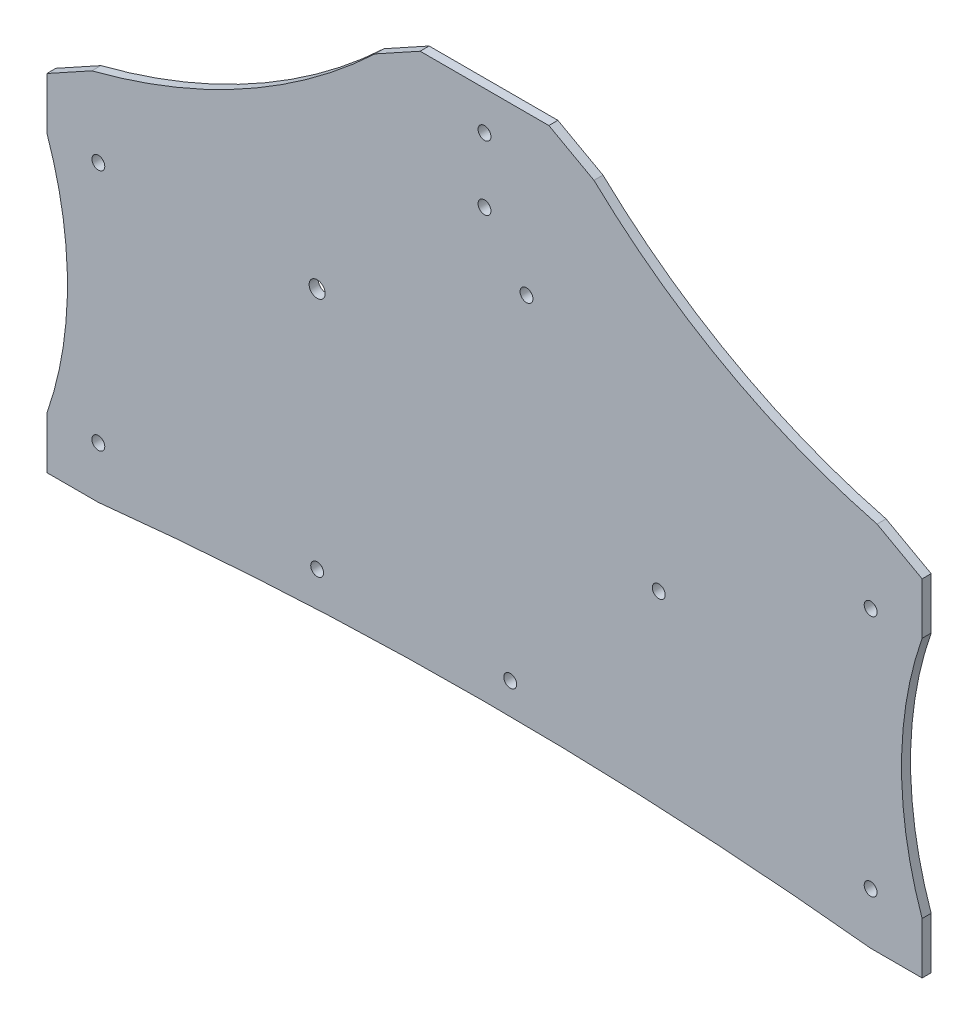
SolidWorks part; units mm, degrees
material "Cedar"
ref_plane "Front Plane" through (0, 0, 0) normal (0, 0, 1) x (1, 0, 0)
ref_plane "Top Plane" through (0, 0, 0) normal (0, 1, 0) x (1, 0, 0)
ref_plane "Right Plane" through (0, 0, 0) normal (1, 0, 0) x (0, 0, -1)
sketch "Sketch2" plane through (0, 0, 0) normal (0, 0, 1) x (1, 0, 0)
  line L1 (401.8817, -319.4711) -> (-233.1183, -319.4711)
  line L2 (401.8817, -319.4711) -> (401.8817, 315.5289)
  line L3 (401.8817, 315.5289) -> (-233.1183, 315.5289)
  line L4 (-233.1183, -319.4711) -> (-233.1183, 315.5289)
  line L5 (401.8817, -319.4711) -> (-233.1183, 315.5289) construction
  line L6 (401.8817, 315.5289) -> (-233.1183, -319.4711) construction
  point P0 (41.2053, 41.2053)
  dimension "D1" = 635
  dimension "D2" = 635
extrude "Boss-Extrude3" add sketch "Sketch2" along normal blind 4.445
sketch "Sketch3" plane through (0, 0, 0) normal (0, 0, -1) x (-1, 0, 0)
  circle A0 centre (-130.0265, 72.4535) radius 3.175
  circle A1 centre (-195.2881, -21.3837) radius 3.175
  circle A2 centre (-122.0047, -96.2659) radius 3.175
  circle A3 centre (-26.7547, -96.2659) radius 3.175
  circle A4 centre (-26.7547, 23.4697) radius 3.9751
  circle A5 centre (81.1953, -96.2659) radius 3.175
  circle A6 centre (-299.8047, -96.2659) radius 3.175
  circle A7 centre (81.1953, 23.4697) radius 3.175
  circle A8 centre (-299.8047, 23.4697) radius 3.175
  point P23 (-195.2881, -21.3837)
  point P24 (-130.0265, 72.4535)
  dimension "D1" = 6.35
  dimension "D2" = 6.35
  dimension "D3" = 6.35
  dimension "D4" = 6.35
  dimension "D5" = 7.9502
  dimension "D6" = 203.2
  dimension "D7" = 177.8
extrude "Cut-Extrude1" cut sketch "Sketch3" against normal through all
sketch "Sketch5" plane through (0, 0, 4.445) normal (0, 0, 1) x (1, 0, 0)
  line L0 (-106.5953, -121.6659) -> (325.2047, -121.6659)
  line L1 (-106.5953, -121.6659) -> (-106.5953, 48.8697)
  line L2 (77.5547, 150.4697) -> (-106.5953, 48.8697)
  line L3 (141.0547, 150.4697) -> (325.2047, 48.8697)
  line L5 (-106.5953, 48.8697) -> (325.2047, 48.8697) construction
  line L6 (77.5547, 150.4697) -> (141.0547, 150.4697)
  line L7 (325.2047, 48.8697) -> (325.2047, -121.6659)
  line L9 (-233.1183, 315.5289) -> (401.8817, 315.5289)
  line L10 (-233.1183, 315.5289) -> (-233.1183, -319.4711)
  line L11 (-233.1183, -319.4711) -> (401.8817, -319.4711)
  line L12 (401.8817, 315.5289) -> (401.8817, -319.4711)
  circle A0 centre (122.0047, -96.2659) radius 3.175 construction
  circle A1 centre (-81.1953, -96.2659) radius 3.175 construction
  circle A3 centre (299.8047, 23.4697) radius 3.175 construction
  circle A5 centre (-81.1953, 23.4697) radius 3.175 construction
  point P11 (109.3047, 48.8697)
  point P19 (130.0265, 72.4535)
  point P25 (109.3047, 150.4697)
  dimension "D1" = 25.4
  dimension "D2" = 25.4
  dimension "D3" = 25.4
  dimension "D4" = 25.4
  dimension "D5" = 101.6
  dimension "D6" = 63.5
  dimension "D7" = 25.4
extrude "Cut-Extrude2" cut sketch "Sketch5" against normal through all
sketch "Sketch7" plane through (0, 0, 4.445) normal (0, 0, 1) x (1, 0, 0)
  line L0 (-81.1953, 23.4697) -> (26.7547, -96.2659) construction
  line L1 (-106.5953, -121.6659) -> (325.2047, -121.6659) construction
  line L2 (-106.5953, -121.6659) -> (-106.5953, 48.8697) construction
  line L3 (77.5547, 150.4697) -> (-106.5953, 48.8697) construction
  line L4 (141.0547, 150.4697) -> (325.2047, 48.8697) construction
  line L5 (325.2047, 48.8697) -> (325.2047, -121.6659) construction
  line L6 (-106.5953, -121.6659) -> (-106.5953, 48.8697) construction
  line L7 (-106.5953, 23.4697) -> (-106.5953, -96.2659)
  line L8 (-81.1953, -121.6659) -> (299.8047, -121.6659)
  line L9 (325.2047, -96.2659) -> (325.2047, 23.4697)
  line L10 (-84.3557, 61.1399) -> (55.315, 138.1995)
  line L11 (163.2943, 138.1995) -> (302.965, 61.1399)
  circle A0 centre (-27.2203, -36.3981) radius 53.975
  circle A1 centre (74.1068, -63.0664) radius 37.1573
  circle A2 centre (81.6247, 49.3691) radius 22.534
  circle A3 centre (255.1128, 8.0341) radius 28.2634
  circle A4 centre (205.4689, -79.3657) radius 26.9434
  circle A5 centre (148.2473, -57.5972) radius 24.9537
  circle A6 centre (194.1429, 16.0636) radius 19.2001
  circle A7 centre (272.6512, -57.5972) radius 27.3858
  circle A8 centre (130.0295, 5.832) radius 31.1244
  circle A9 centre (184.8075, 59.9881) radius 14.5989
  circle A10 centre (63.5186, 0) radius 18.4298
  arc A11 (-81.1953, -121.6659) -> (299.8047, -121.6659) centre (109.3047, -1902.5234) cw
  arc A12 (-106.5953, -96.2659) -> (-106.5953, 23.4697) centre (-277.9008, -36.3981) ccw
  arc A13 (-84.3557, 61.1399) -> (55.315, 138.1995) centre (-163.3019, 369.3362) ccw
  arc A14 (163.2943, 138.1995) -> (302.965, 61.1399) centre (381.9112, 369.3362) ccw
  arc A15 (325.2047, 23.4697) -> (325.2047, -96.2659) centre (496.5102, -36.3981) ccw
  point P14 (-27.2203, -36.3981)
  point P15 (-81.1953, -36.3981)
  point P28 (255.1128, 8.0341)
  point P47 (-9.6123, 90.7738)
  point P51 (228.2216, 90.7738)
  point P58 (315.0447, -36.3981)
  point P59 (109.3047, -111.5059)
  point P60 (-96.4353, -36.3981)
  dimension "D1" = 25.4
  dimension "D2" = 10.16
  dimension "D9" = 25.4
  dimension "D3" = 25.4
  dimension "D4" = 25.4
  dimension "D5" = 25.4
  dimension "D6" = 25.4
  dimension "D7" = 25.4
  dimension "D8" = 25.4
  dimension "D10" = 25.4
  dimension "D11" = 25.4
  dimension "D12" = 25.4
  dimension "D13" = 10.16
  dimension "D14" = 10.16
  dimension "D15" = 10.16
  dimension "D16" = 10.16
extrude "Cut-Extrude3" cut sketch "Sketch7" against normal through all
sketch "Sketch9" plane through (0, 0, 4.445) normal (0, 0, 1) x (1, 0, 0)
  line L0 (82.9137, 23.4697) -> (-29.4044, 23.4697) construction
  circle A0 centre (82.9137, 23.4697) radius 1.7526
  circle A1 centre (-29.4044, 23.4697) radius 1.7526
  point P4 (26.7547, 23.4697)
  dimension "D1" = 3.5052
  dimension "D2" = 3.5052
  dimension "D3" = 112.318
extrude "Cut-Extrude4" [suppressed] cut sketch "Sketch9" against normal through all
sketch "Sketch10" plane through (0, 0, 4.445) normal (0, 0, 1) x (1, 0, 0)
  line L0 (109.3047, 150.4697) -> (109.3047, -111.5059) construction
  line L1 (77.5547, 150.4697) -> (141.0547, 150.4697) construction
  arc A0 (299.8047, -121.6659) -> (-81.1953, -121.6659) centre (109.3047, -1902.5234) ccw construction
  circle A1 centre (109.3047, 131.4197) radius 3.175
  circle A2 centre (109.3047, 99.6697) radius 3.175
  dimension "D1" = 6.35
  dimension "D2" = 6.35
  dimension "D3" = 19.05
  dimension "D4" = 31.75
extrude "Cut-Extrude5" cut sketch "Sketch10" against normal through all
